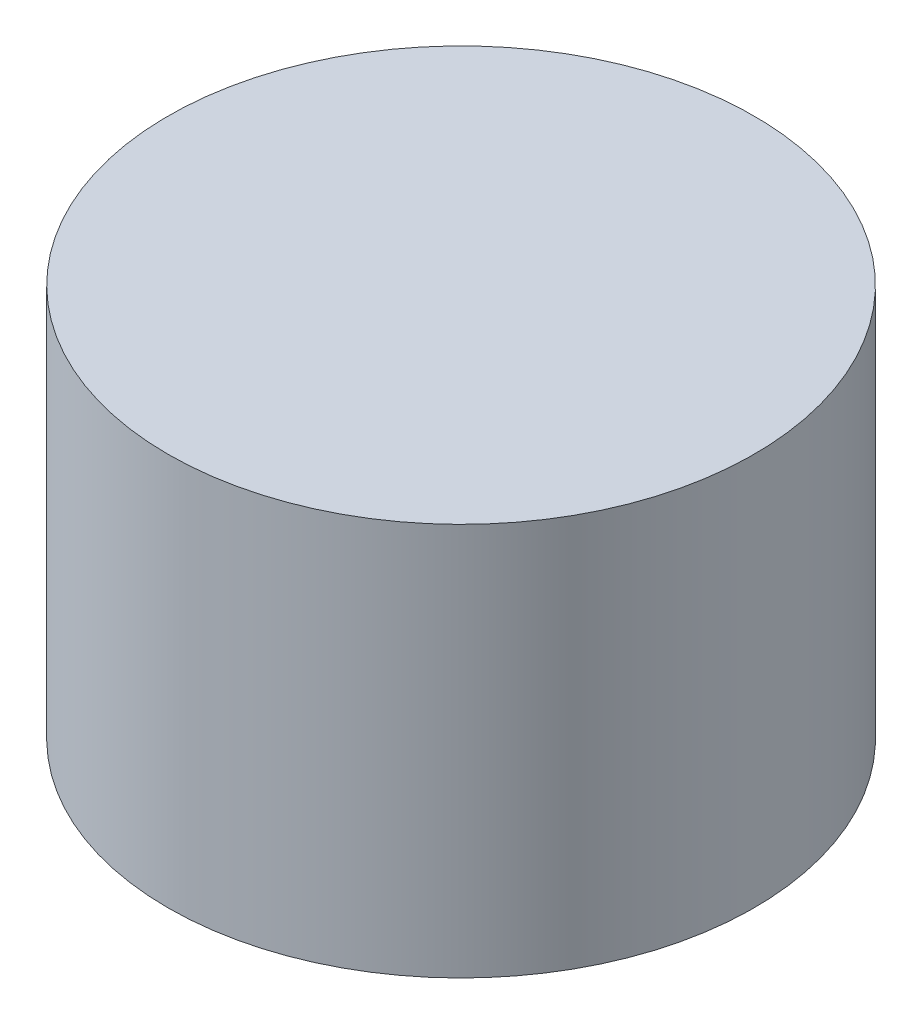
SolidWorks part; units mm, degrees
ref_plane "Front Plane" through (0, 0, 0) normal (0, 0, 1) x (1, 0, 0)
ref_plane "Top Plane" through (0, 0, 0) normal (0, 1, 0) x (1, 0, 0)
ref_plane "Right Plane" through (0, 0, 0) normal (1, 0, 0) x (0, 0, -1)
sketch "Sketch1" plane through (0, 0, 0) normal (0, 1, 0) x (1, 0, 0)
  circle A0 centre (0, 0) radius 8.95
  dimension "D1" = 17.9
extrude "Boss-Extrude1" add sketch "Sketch1" along normal blind 12
